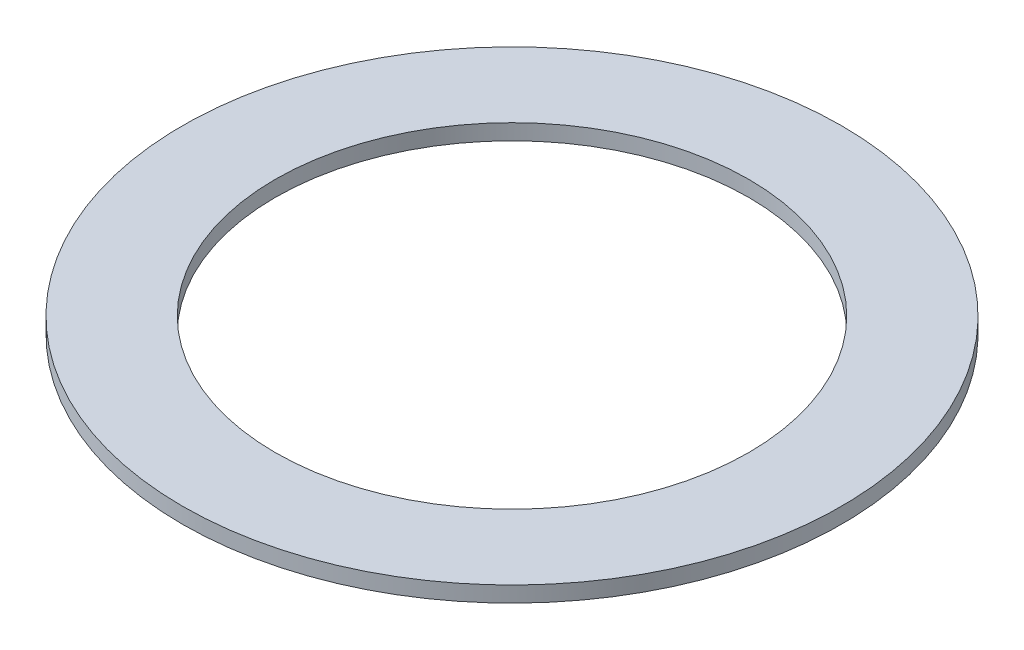
SolidWorks part; units mm, degrees
ref_plane "Front Plane" through (0, 0, 0) normal (0, 0, 1) x (1, 0, 0)
ref_plane "Top Plane" through (0, 0, 0) normal (0, 1, 0) x (1, 0, 0)
ref_plane "Right Plane" through (0, 0, 0) normal (1, 0, 0) x (0, 0, -1)
sketch "Sketch1" plane through (0, 0, 0) normal (0, 1, 0) x (1, 0, 0)
  line L0 (0, -41.439) -> (0, 59.5224) construction
  line L1 (-42.487, -10.5704) -> (53.5331, 20.6284) construction
  line L2 (-26.2584, 39.3761) -> (33.0853, -42.3035) construction
  line L3 (26.2584, 39.3761) -> (-33.0853, -42.3035) construction
  line L4 (42.487, -10.5704) -> (-53.5331, 20.6284) construction
  line L5 (0, 3.2345) -> (0, -41.439) construction
  circle A0 centre (0, 0) radius 31.5
  circle A1 centre (0, 0) radius 22.625
  point P4 (0, 24.1)
  dimension "D1" = 63
  dimension "D2" = 45.25
  dimension "D3" = 24.1
  dimension "D4" = 5
  dimension "D5" = 44.6735
extrude "Boss-Extrude1" add sketch "Sketch1" along normal blind 1.5
